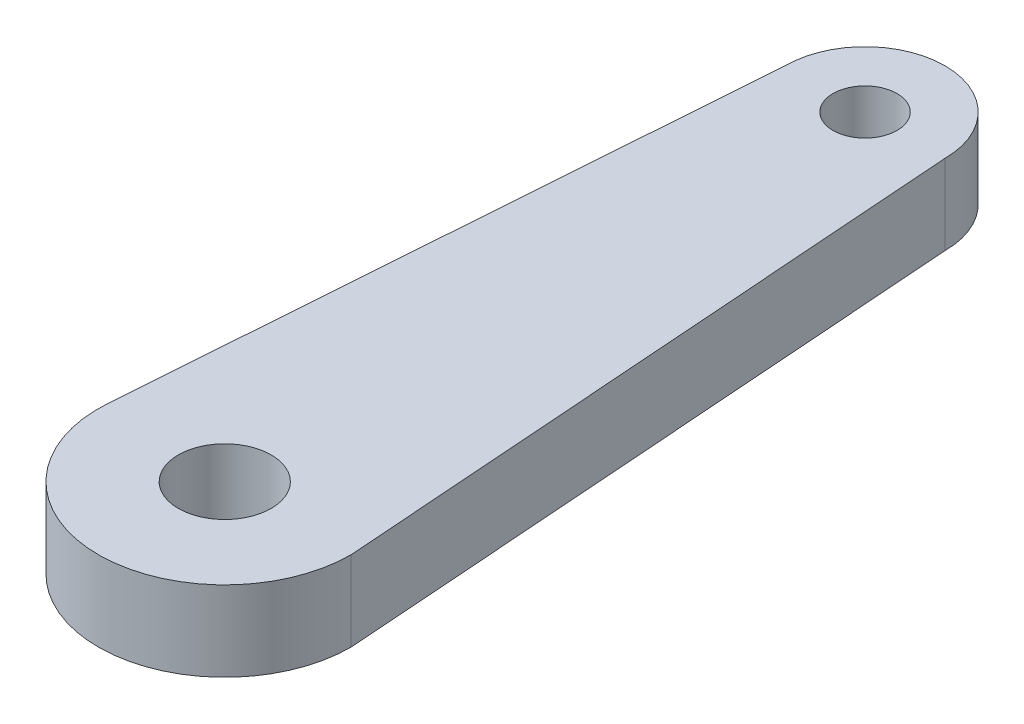
SolidWorks part; units mm, degrees
ref_plane "Front" through (0, 0, 0) normal (0, 0, 1) x (1, 0, 0)
ref_plane "Top" through (0, 0, 0) normal (0, 1, 0) x (1, 0, 0)
ref_plane "Right" through (0, 0, 0) normal (1, 0, 0) x (0, 0, -1)
sketch "Sketch1" plane through (0, 0, 0) normal (0, 1, 0) x (1, 0, 0)
  line L0 (-7.879, 0.5754) -> (-5, 40)
  line L1 (5, 40) -> (7.9, 0)
  circle A0 centre (0, 0) radius 2.9
  arc A1 (-7.879, 0.5754) -> (7.8174, 1.1395) centre (0, 0) ccw
  arc A2 (5, 40) -> (-5, 40) centre (0, 40) ccw
  circle A3 centre (0, 40) radius 2
  dimension "D2" = 5.8
  dimension "D3" = 5
  dimension "D4" = 3
  dimension "D5" = 4
  dimension "D1" = 40
extrude "Boss-Extrude1" add sketch "Sketch1" along normal blind 5 contours L1 A2 L0 A1 A3 A0
